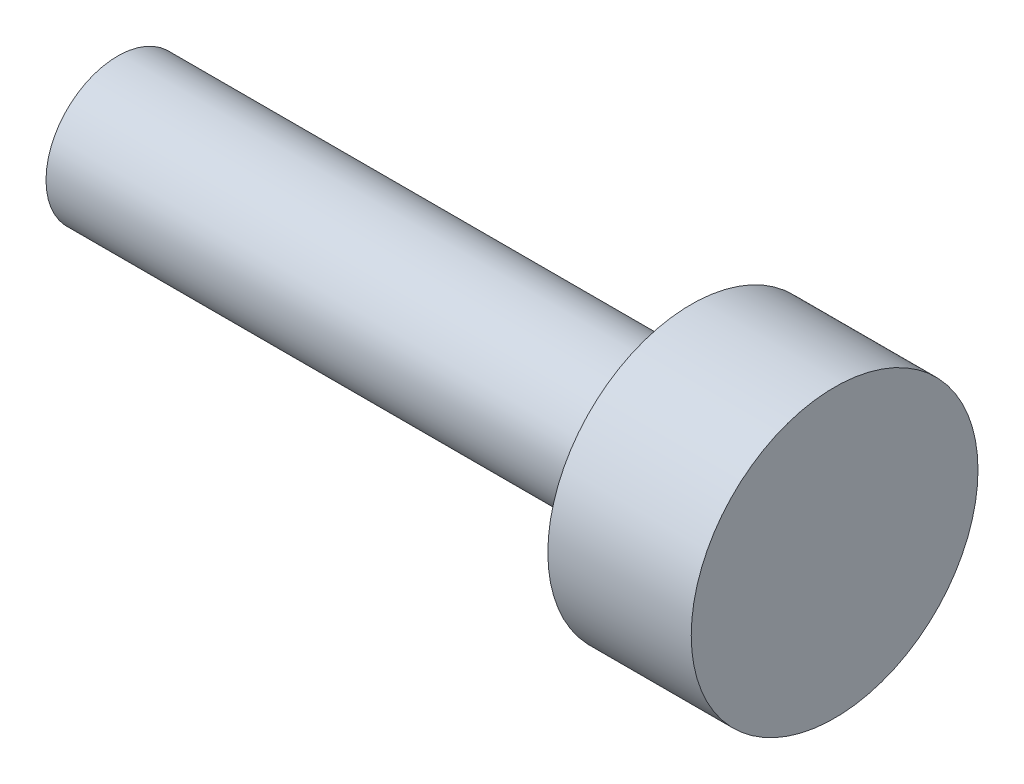
SolidWorks part; units mm, degrees
ref_plane "Front Plane" through (0, 0, 0) normal (0, 0, 1) x (1, 0, 0)
ref_plane "Top Plane" through (0, 0, 0) normal (0, 1, 0) x (1, 0, 0)
ref_plane "Right Plane" through (0, 0, 0) normal (1, 0, 0) x (0, 0, -1)
sketch "Sketch1" plane through (0, 0, 0) normal (0, 0, 1) x (1, 0, 0)
  line L0 (-116.8358, 27.1754) -> (-105.8358, 27.1754)
  line L1 (-105.8358, 27.1754) -> (-105.8358, 28.1754)
  line L2 (-105.8358, 28.1754) -> (-103.8358, 28.1754)
  line L3 (-103.8358, 28.1754) -> (-103.8358, 26.1754)
  line L4 (-116.8358, 27.1754) -> (-116.8358, 26.1754)
  line L5 (-116.8358, 26.1754) -> (-103.8358, 26.1754) construction
  line L6 (-103.8358, 26.1754) -> (-116.8358, 26.1754)
revolve "Revolve1" add sketch "Sketch1" angle 360 about L5
sketch "Sketch2" plane through (-116.8358, 0, 0) normal (-1, 0, 0) x (0, 0, 1)
  line L1 (-1.174, 27.3227) -> (1.2121, 27.3227)
  line L2 (-1.174, 27.3227) -> (-1.174, 25.0738)
  line L3 (-1.174, 25.0738) -> (1.2121, 25.0738)
  line L4 (1.2121, 27.3227) -> (1.2121, 25.0738)
extrude "Cut-Extrude1" cut sketch "Sketch2" against normal blind 3
